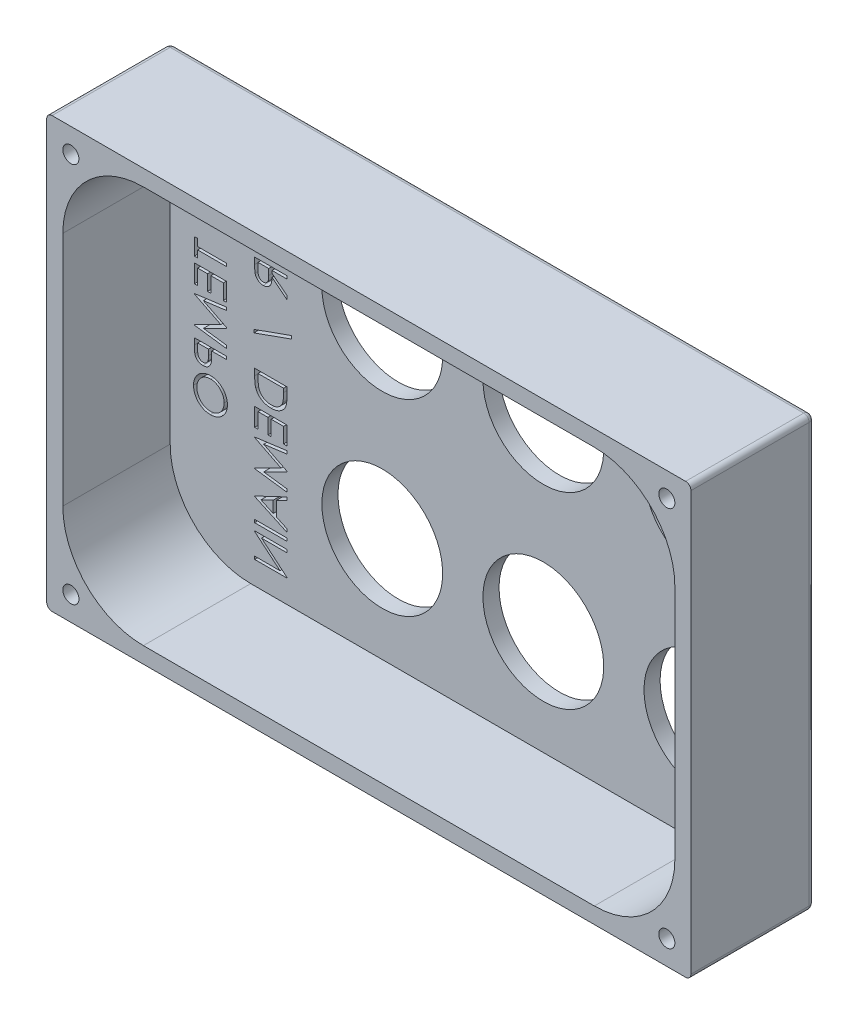
SolidWorks part; units mm, degrees
ref_plane "Plan de face" through (0, 0, 0) normal (0, 0, 1) x (1, 0, 0)
ref_plane "Plan de dessus" through (0, 0, 0) normal (0, 1, 0) x (1, 0, 0)
ref_plane "Plan de droite" through (0, 0, 0) normal (1, 0, 0) x (0, 0, -1)
sketch "Esquisse1" plane through (0, 0, 0) normal (0, 0, 1) x (1, 0, 0)
  line L1 (0, 0) -> (120, 0)
  line L2 (0, 0) -> (0, 80)
  line L3 (0, 80) -> (120, 80)
  line L4 (120, 0) -> (120, 80)
  dimension "D1" = 120
  dimension "D2" = 80
extrude "Boss.-Extru.1" add sketch "Esquisse1" along normal blind 3
sketch "Esquisse4" plane through (0, 0, 3) normal (0, 0, 1) x (1, 0, 0)
  line L1 (0, 80) -> (120, 80)
  line L2 (0, 80) -> (0, 0)
  line L3 (0, 0) -> (120, 0)
  line L4 (120, 80) -> (120, 0)
  line L5 (3, 77) -> (117, 77)
  line L6 (3, 77) -> (3, 3)
  line L7 (3, 3) -> (117, 3)
  line L8 (117, 77) -> (117, 3)
  dimension "D1" = 3
  dimension "D2" = 3
  dimension "D3" = 3
  dimension "D4" = 3
extrude "Boss.-Extru.3" add sketch "Esquisse4" along normal blind 20
fillet "Congé1" radius 15 4 edges at (3, 3, 13) (117, 3, 13) (117, 77, 13) (3, 77, 13)
sketch "Esquisse5" plane through (0, 0, 23) normal (0, 0, 1) x (1, 0, 0)
  line L0 (120, 80) -> (0, 80) construction
  line L1 (0, 80) -> (0, 0) construction
  line L2 (120, 0) -> (120, 80) construction
  line L3 (0, 0) -> (120, 0) construction
  circle A0 centre (4.5, 75.5) radius 1.5
  circle A1 centre (115.5, 75.5) radius 1.5
  circle A2 centre (115.5, 4.5) radius 1.5
  circle A3 centre (4.5, 4.5) radius 1.5
  dimension "D1" = 3
  dimension "D2" = 4.5
  dimension "D3" = 4.5
  dimension "D4" = 4.5
  dimension "D5" = 4.5
  dimension "D6" = 4.5
  dimension "D7" = 4.5
  dimension "D8" = 4.5
  dimension "D9" = 4.5
extrude "Enlèv. mat.-Extru.1" cut sketch "Esquisse5" against normal blind 15
sketch "Esquisse6" plane through (0, 0, 0) normal (0, 0, -1) x (-1, 0, 0)
  line L0 (-120, 80) -> (0, 80) construction
  line L1 (0, 0) -> (-120, 0) construction
  line L2 (-120, 0) -> (-120, 80) construction
  line L3 (-13.5, 80) -> (-13.5, 0) construction
  circle A0 centre (-102.5, 57.5) radius 11.25
  circle A1 centre (-72.5, 57.5) radius 11.25
  circle A2 centre (-42.5, 57.5) radius 11.25
  circle A3 centre (-42.5, 22.5) radius 11.25
  circle A4 centre (-72.5, 22.5) radius 11.25
  circle A5 centre (-102.5, 22.5) radius 11.25
  text T0 "TEMPO\r\nJOUR  /  DEMAIN" font "Century Gothic" height 6
  dimension "D1" = 22.5
  dimension "D2" = 22.5
  dimension "D3" = 22.5
  dimension "D4" = 17.5
  dimension "D5" = 30
  dimension "D6" = 30
  dimension "D7" = 29
extrude "Enlèv. mat.-Extru.2" cut sketch "Esquisse6" against normal through all
fillet "Congé2" radius 1 8 edges at (0, 80, 11.5) (120, 80, 11.5) (60, 80, 0) (120, 40, 0) (120, 0, 11.5) (0, 0, 11.5) (60, 0, 0) (0, 40, 0)
